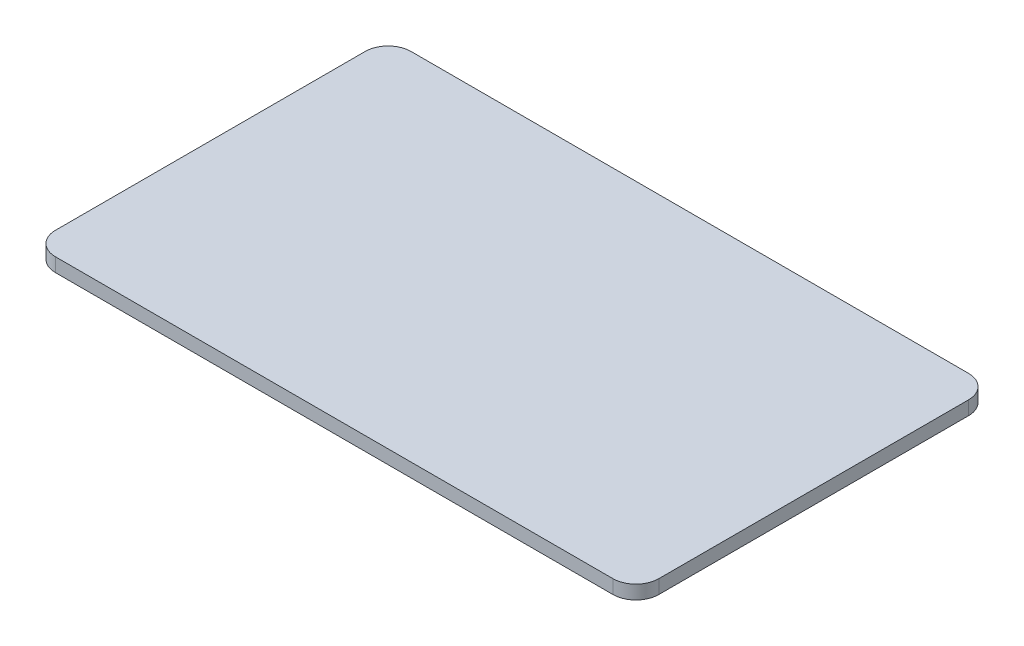
SolidWorks part; units mm, degrees
ref_plane "Front Plane" through (0, 0, 0) normal (0, 0, 1) x (1, 0, 0)
ref_plane "Top Plane" through (0, 0, 0) normal (0, 1, 0) x (1, 0, 0)
ref_plane "Right Plane" through (0, 0, 0) normal (1, 0, 0) x (0, 0, -1)
sketch "Sketch1" plane through (0, 0, 0) normal (0, 1, 0) x (1, 0, 0)
  line L0 (-58.7361, -27.1269) -> (95.5689, -27.1269)
  line L1 (101.9189, -20.7769) -> (101.9189, 64.9481)
  line L2 (95.5689, 71.2981) -> (-58.7361, 71.2981)
  line L3 (-65.0861, 64.9481) -> (-65.0861, -20.7769)
  arc A0 (-65.0861, -20.7769) -> (-58.7361, -27.1269) centre (-58.7361, -20.7769) ccw
  arc A1 (-58.7361, 71.2981) -> (-65.0861, 64.9481) centre (-58.7361, 64.9481) ccw
  arc A2 (101.9189, 64.9481) -> (95.5689, 71.2981) centre (95.5689, 64.9481) ccw
  arc A3 (95.5689, -27.1269) -> (101.9189, -20.7769) centre (95.5689, -20.7769) ccw
extrude "Boss-Extrude1" add sketch "Sketch1" along normal blind 3.81
